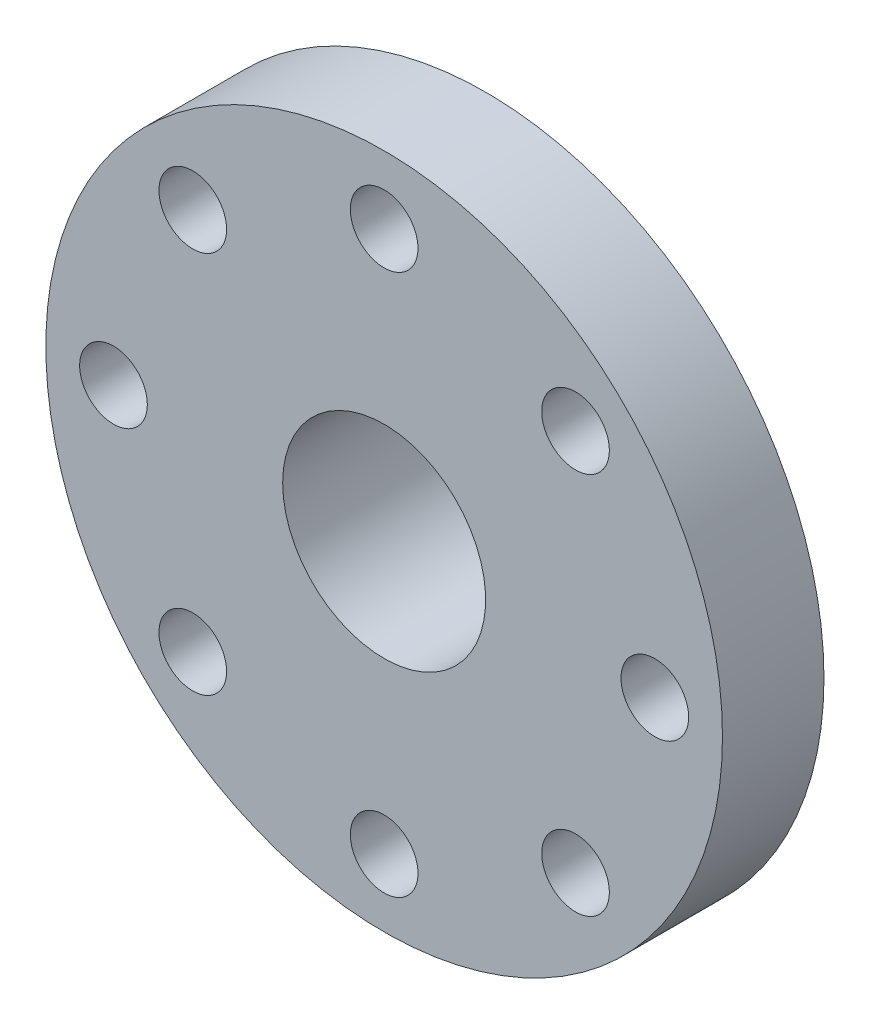
SolidWorks part; units mm, degrees
material "6061 合金"
ref_plane "前视基准面" through (0, 0, 0) normal (0, 0, 1) x (1, 0, 0)
ref_plane "上视基准面" through (0, 0, 0) normal (0, 1, 0) x (1, 0, 0)
ref_plane "右视基准面" through (0, 0, 0) normal (1, 0, 0) x (0, 0, -1)
sketch "草图1" plane through (0, 0, 0) normal (0, 0, 1) x (1, 0, 0)
  line L0 (0, 0) -> (0, 16) construction
  line L1 (0, 16) -> (0, -19.3956) construction
  line L2 (0, -19.3956) -> (0, 0) construction
  line L3 (0, 0) -> (-16.7859, 0) construction
  line L4 (-16.7859, 0) -> (19.82, 0) construction
  line L5 (19.82, 0) -> (19.82, -0.2042) construction
  line L7 (0, 0) -> (0, -7) construction
  circle A0 centre (0, 0) radius 10
  circle A1 centre (0, 0) radius 1.5
  circle A2 centre (0, 8) radius 1
  circle A3 centre (5.6569, 5.6569) radius 1
  circle A4 centre (8, 0) radius 1
  circle A5 centre (5.6569, -5.6569) radius 1
  circle A6 centre (0, -8) radius 1
  circle A7 centre (-5.6569, -5.6569) radius 1
  circle A8 centre (-8, 0) radius 1
  circle A9 centre (-5.6569, 5.6569) radius 1
  point P28 (0, 0)
  dimension "D1" = 8
  dimension "D2" = 8
  dimension "D3" = 20
  dimension "D4" = 2
  dimension "D5" = 3
extrude "凸台-拉伸1" add sketch "草图1" along normal blind 3
sketch "草图2" plane through (0, 0, 0) normal (0, 0, -1) x (-1, 0, 0)
  circle A0 centre (0, 0) radius 5
  dimension "D1" = 10
extrude "凸台-拉伸2" add sketch "草图2" along normal blind 2
sketch "草图3" plane through (0, 0, -2) normal (0, 0, -1) x (-1, 0, 0)
  circle A0 centre (0, 0) radius 3
extrude "切除-拉伸1" cut sketch "草图3" against normal through all
chamfer "倒角1" [suppressed] distance 0.5 angle 45
